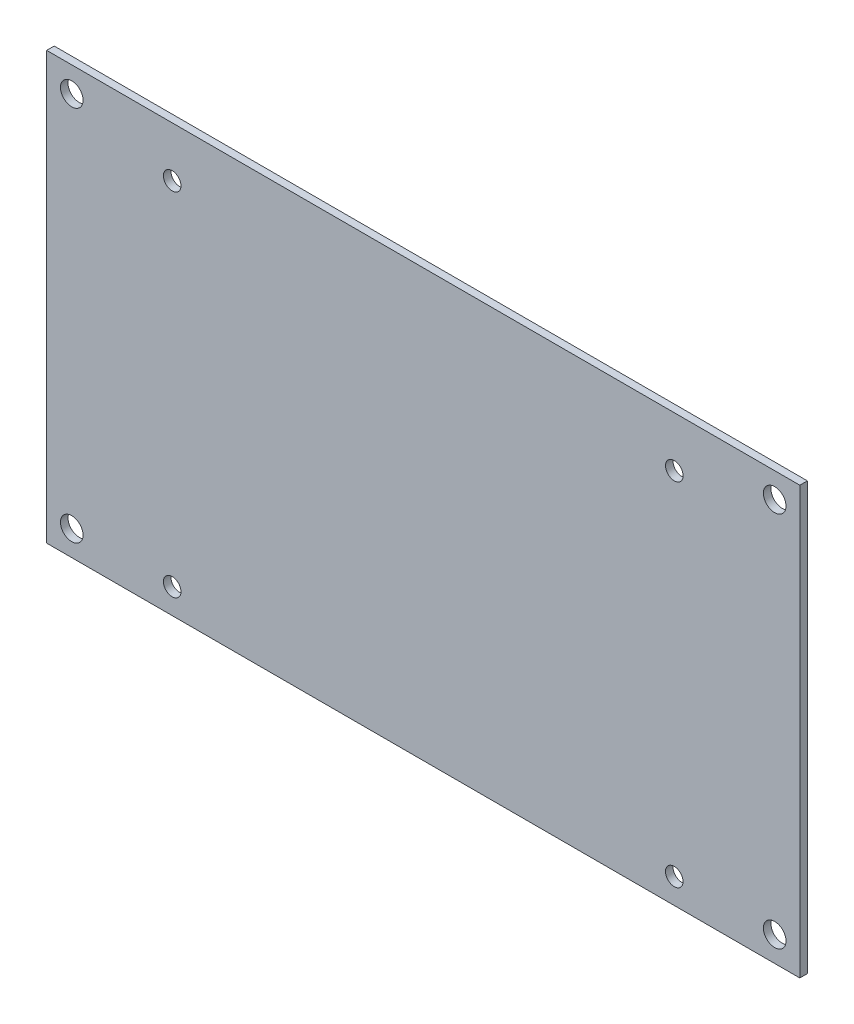
SolidWorks part; units mm, degrees
ref_plane "Спереди" through (0, 0, 0) normal (0, 0, 1) x (1, 0, 0)
ref_plane "Сверху" through (0, 0, 0) normal (0, 1, 0) x (1, 0, 0)
ref_plane "Справа" through (0, 0, 0) normal (1, 0, 0) x (0, 0, -1)
sketch "Эскиз1" plane through (0, 0, 0) normal (0, 0, 1) x (1, 0, 0)
  line L0 (0, 42.3611) -> (0, -41.9385) construction
  line L1 (0, 0) -> (-35.1574, 0) construction
  line L2 (50, -37.5) -> (50, 32.5) construction
  line L3 (-75, -42.5) -> (75, -42.5)
  line L4 (-75, -42.5) -> (-75, 42.5)
  line L5 (-75, 42.5) -> (75, 42.5)
  line L6 (75, -42.5) -> (75, 42.5)
  circle A0 centre (-70, 37.5) radius 2.25
  circle A1 centre (-70, -37.5) radius 2.25
  circle A2 centre (70, -37.5) radius 2.25
  circle A3 centre (70, 37.5) radius 2.25
  circle A4 centre (-50, 32.5) radius 1.75
  circle A5 centre (-50, -37.5) radius 1.75
  circle A6 centre (50, 32.5) radius 1.75
  circle A7 centre (50, -37.5) radius 1.75
  dimension "D3" = 75
  dimension "D5" = 140
  dimension "D8" = 3.5
  dimension "D10" = 70
  dimension "D4" = 5
  dimension "D7" = 100
  dimension "D6" = 70
  dimension "D12" = 100
  dimension "D9" = 4.5
  dimension "D1" = 150
  dimension "D2" = 85
extrude "Вытянуть1" add sketch "Эскиз1" along normal blind 1.5
